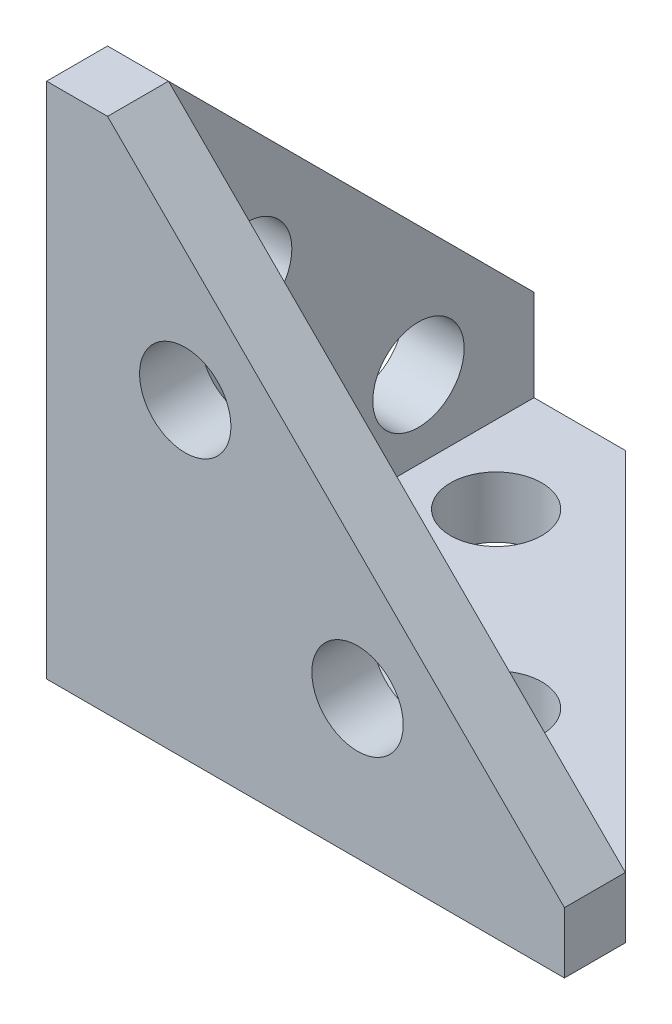
SolidWorks part; units mm, degrees
ref_plane "Ön Düzlem" through (0, 0, 0) normal (0, 0, 1) x (1, 0, 0)
ref_plane "Üst Düzlem" through (0, 0, 0) normal (0, 1, 0) x (1, 0, 0)
ref_plane "Sağ Düzlem" through (0, 0, 0) normal (1, 0, 0) x (0, 0, -1)
sketch "Sketch1" plane through (0, 0, 0) normal (0, 1, 0) x (1, 0, 0)
  line L0 (0, 15) -> (15, 0)
  line L1 (0, 0) -> (15, 0)
  line L2 (0, 0) -> (0, 15)
  dimension "D1" = 15
  dimension "D2" = 15
extrude "Boss-Extrude1" add sketch "Sketch1" along normal blind 2
sketch "Sketch2" plane through (0, 2, 0) normal (0, 1, 0) x (1, 0, 0)
  line L0 (-2, -2) -> (15, -2)
  line L1 (0, 15) -> (-2, 15)
  line L2 (0, 15) -> (0, 0)
  line L4 (-2, 15) -> (-2, -2)
  line L5 (15, -2) -> (15, 0)
  line L6 (15, 0) -> (0, 0)
  dimension "D1" = 2
  dimension "D2" = 2
extrude "Boss-Extrude2" add sketch "Sketch2" along normal blind 15 and the other way blind 2
sketch "Sketch3" plane through (0, 0, 0) normal (1, 0, 0) x (0, 0, -1)
  line L0 (15, 2) -> (0, 17)
  line L1 (0, 17) -> (15, 17)
  line L2 (15, 17) -> (15, 2)
extrude "Cut-Extrude1" cut sketch "Sketch3" against normal blind 15
sketch "Sketch4" plane through (0, 0, 0) normal (0, 0, -1) x (-1, 0, 0)
  line L0 (0, 17) -> (-15, 2)
  line L1 (-15, 2) -> (-15, 17)
  line L2 (-15, 17) -> (0, 17)
extrude "Cut-Extrude2" cut sketch "Sketch4" against normal blind 15
sketch "Sketch5" plane through (0, 0, 0) normal (1, 0, 0) x (0, 0, -1)
  line L0 (0, 12.7574) -> (10.7574, 2) construction
  line L1 (0, 2) -> (0, 17) construction
  line L2 (15, 2) -> (0, 2) construction
  line L3 (0, 17) -> (15, 2) construction
  line L4 (5.3787, 7.3787) -> (7.5, 9.5) construction
  circle A0 centre (2.5503, 10.2071) radius 1.5
  circle A1 centre (8.2071, 4.5503) radius 1.5
  dimension "D2" = 3
  dimension "D1" = 3
  dimension "D3" = 8
extrude "Cut-Extrude3" cut sketch "Sketch5" against normal blind 15
sketch "Sketch6" plane through (0, 0, 0) normal (0, 0, -1) x (-1, 0, 0)
  line L0 (-10.7574, 2) -> (0, 12.7574) construction
  line L1 (-15, 2) -> (0, 2) construction
  line L2 (0, 17) -> (0, 2) construction
  line L3 (-15, 2) -> (0, 17) construction
  line L4 (-5.3787, 7.3787) -> (-7.5, 9.5) construction
  circle A0 centre (-2.5503, 10.2071) radius 1.5
  circle A1 centre (-8.2071, 4.5503) radius 1.5
  dimension "D2" = 3
  dimension "D1" = 3
  dimension "D3" = 8
extrude "Cut-Extrude4" cut sketch "Sketch6" against normal blind 15
sketch "Sketch7" plane through (0, 2, 0) normal (0, 1, 0) x (1, 0, 0)
  line L0 (0, 10.7574) -> (10.7574, 0) construction
  line L1 (0, 15) -> (0, 0) construction
  line L2 (15, 0) -> (0, 0) construction
  line L3 (5.3787, 5.3787) -> (7.5, 7.5) construction
  line L4 (15, 0) -> (0, 15) construction
  circle A0 centre (2.5503, 8.2071) radius 1.5
  circle A1 centre (8.2071, 2.5503) radius 1.5
  dimension "D2" = 3
  dimension "D1" = 3
  dimension "D3" = 8
extrude "Cut-Extrude5" cut sketch "Sketch7" against normal blind 15
sketch "Çizim1" plane through (0, 0, -15) normal (0, 0, -1) x (-1, 0, 0)
  line L0 (0, 17) -> (2, 17) construction
  line L1 (2, 0) -> (-15, 0)
  line L2 (2, 0) -> (2, 17)
  line L3 (2, 17) -> (-15, 17)
  line L4 (-15, 0) -> (-15, 17)
  line L5 (-15, 2) -> (-15, 0) construction
extrude "Kes-Ekstrüzyon1" cut sketch "Çizim1" against normal blind 3
